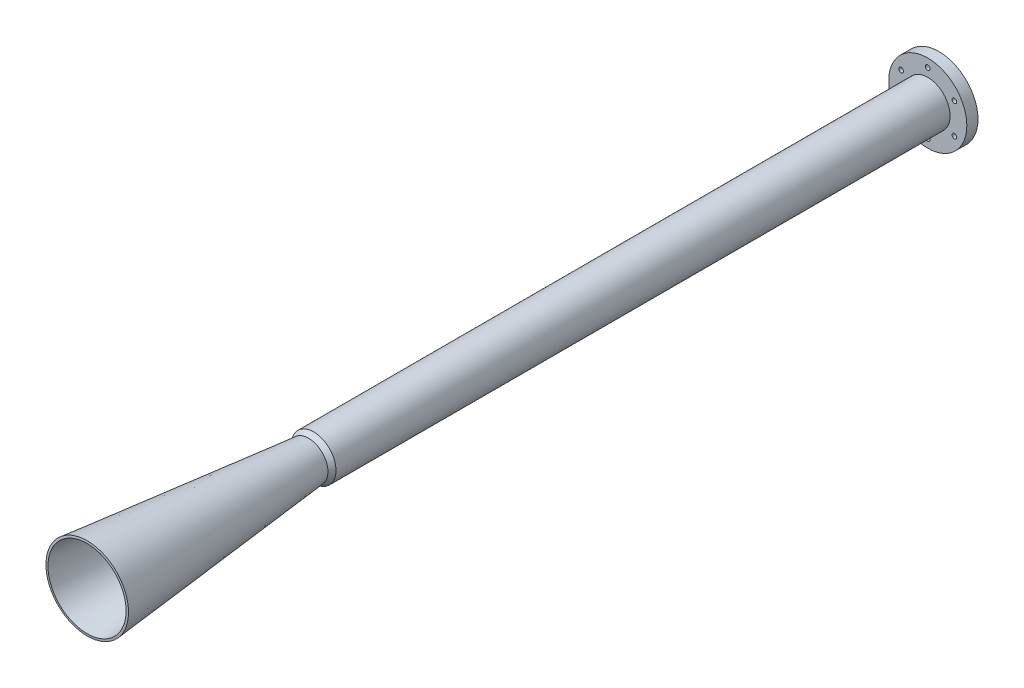
SolidWorks part; units mm, degrees
ref_plane "Спереди" through (0, 0, 0) normal (0, 0, 1) x (1, 0, 0)
ref_plane "Сверху" through (0, 0, 0) normal (0, 1, 0) x (1, 0, 0)
ref_plane "Справа" through (0, 0, 0) normal (1, 0, 0) x (0, 0, -1)
sketch "Эскиз2" plane through (0, 0, 0) normal (1, 0, 0) x (0, 0, -1)
  line L0 (-753, 35) -> (-450, 5)
  line L1 (-450, 5) -> (-399, 5)
  line L2 (-1181.7299, 0) -> (34.5611, 0) construction
  line L3 (-399, 5) -> (0, 5)
  line L5 (0, 15.1851) -> (0, -10.085) construction
  dimension "D1" = 5
  dimension "D2" = 5.654
  dimension "D3" = 303
  dimension "D4" = 354
  dimension "D5" = 35
  dimension "D6" = 399
revolve "Повернуть-Тонкостенный3" add sketch "Эскиз2" angle 360 about L2 wall 2
sketch "Эскиз8" plane through (0, 0, 0) normal (1, 0, 0) x (0, 0, -1)
  line L2 (0, 5) -> (0, 35)
  line L3 (0, 35) -> (10, 35)
  line L6 (10, 35) -> (10, 15)
  line L9 (10, 15) -> (10, 5)
  line L10 (10, 5) -> (0, 5)
  dimension "D1" = 10
  dimension "D3" = 35
revolve "Повернуть1" add sketch "Эскиз8" angle 360 about L2
sketch "Эскиз9" plane through (0, 0, 0) normal (0, 0, 1) x (1, 0, 0)
  line L1 (0, 0) -> (0, 35) construction
  circle A0 centre (0, 0) radius 35 construction
  circle A1 centre (0, 0) radius 27.5 construction
  point P0 (-23.8157, 13.75)
  point P6 (0, 27.5)
  point P7 (23.8157, 13.75)
  point P8 (23.8157, -13.75)
  point P9 (0, -27.5)
  point P10 (-23.8157, -13.75)
  dimension "D1" = 27.5
  dimension "D3" = 35
  dimension "D2" = 6
sketch "Эскиз10" plane through (0, 0, 0) normal (1, 0, 0) x (0, 0, -1)
  line L0 (0, 20) -> (-550, 20)
  line L1 (0, 0) -> (0, 35) construction
  line L2 (-550, 20) -> (-554.5674, 17.363)
  line L3 (-449.9012, 7) -> (-752.8029, 36.9903) construction
  line L4 (-1181.7299, 0) -> (34.5611, 0) construction
  line L5 (-450, 5) -> (-399, 5) construction
  line L6 (-399, 5) -> (0, 5) construction
  line L7 (54.4086, 0) -> (-871.5669, 0) construction
  point P8 (-871.5669, 0)
  dimension "D1" = 150
  dimension "D2" = 15
  dimension "D3" = 550
revolve "Повернуть-Тонкостенный6" add sketch "Эскиз10" angle 360 about L7 wall 2
hole_wizard "Отверстие обработанное метчиком M51" positions "Эскиз11" profile "Эскиз12" tap size "M5" standard "ISO"
sketch "Эскиз11" plane through (0, 0, 0) normal (0, 0, 1) x (1, 0, 0)
  point P0 (-23.8157, 13.75)
  point P3 (0, 27.5)
  point P6 (23.8157, 13.75)
  point P9 (23.8157, -13.75)
  point P12 (-23.8157, -13.75)
  point P15 (0, -27.5)
sketch "Эскиз12" plane through (-23.8157, 13.75, 0) normal (1, 0, 0) x (0, -1, 0)
  line L0 (0, 0) -> (0, 10)
  line L1 (0, 10) -> (2.1, 10)
  line L2 (2.1, 10) -> (2.1, 0)
  line L5 (2.1, 0) -> (0, 0)
  line L11 (0, -6.35) -> (0, 107.95) construction
  dimension "Диаметр проходного сверла" = 4.2
  dimension "Глубина проходного сверла" = 10
cosmetic thread "Отверстие резьбы1" parameters "D2"=5
cosmetic thread "Отверстие резьбы2" parameters "D2"=5
cosmetic thread "Отверстие резьбы3" parameters "D2"=5
cosmetic thread "Отверстие резьбы4" parameters "D2"=5
cosmetic thread "Отверстие резьбы5" parameters "D2"=5
cosmetic thread "Отверстие резьбы6" parameters "D2"=5
